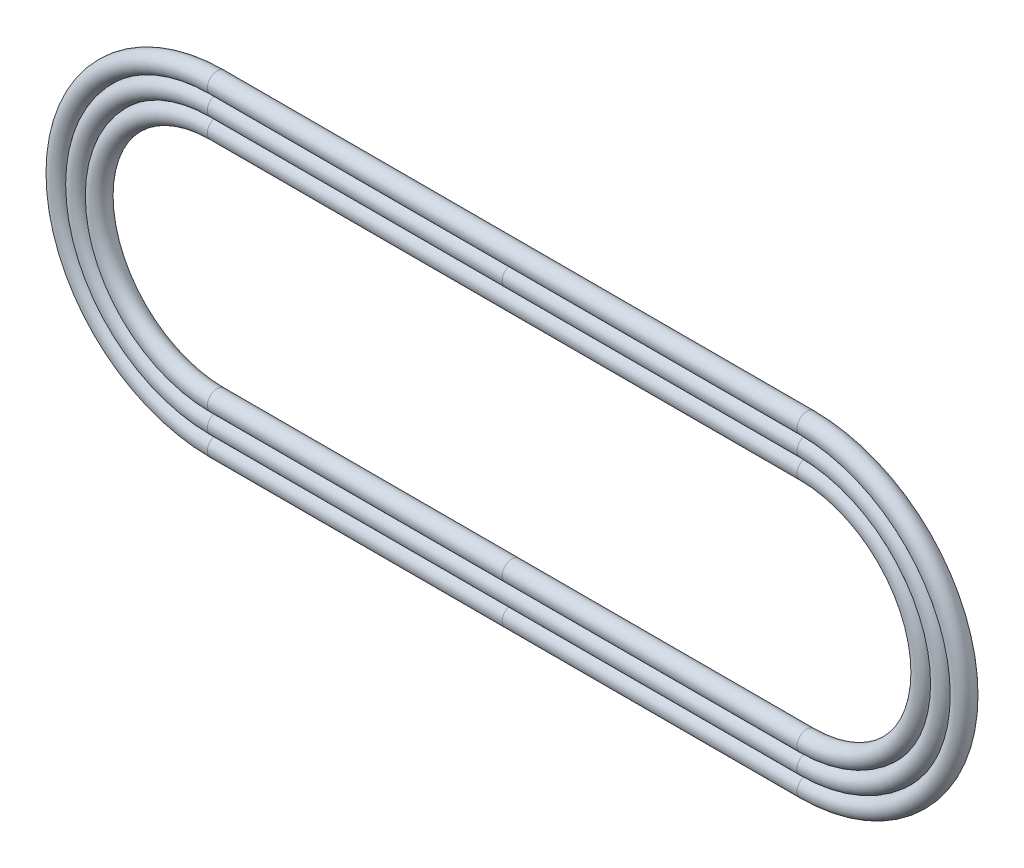
SolidWorks part; units mm, degrees
ref_plane "Front Plane" through (0, 0, 0) normal (0, 0, 1) x (1, 0, 0)
ref_plane "Top Plane" through (0, 0, 0) normal (0, 1, 0) x (1, 0, 0)
ref_plane "Right Plane" through (0, 0, 0) normal (1, 0, 0) x (0, 0, -1)
sketch "Sketch30" plane through (0, 0, 0) normal (0, 0, 1) x (1, 0, 0)
  line L0 (-1500, 0) -> (1500, 0) construction
  line L1 (-1500, 800) -> (1500, 800)
  line L2 (-1500, -800) -> (1500, -800)
  arc A0 (-1500, 800) -> (-1500, -800) centre (-1500, 0) ccw
  arc A1 (1500, -800) -> (1500, 800) centre (1500, 0) ccw
  point P2 (0, 0)
  dimension "D2" = 800
  dimension "D1" = 3000
sketch "Sketch31" plane through (0, 0, 0) normal (1, 0, 0) x (0, 0, -1)
  line L0 (0, 800) -> (0, -800) construction
  line L1 (0, 800) -> (0, -800) construction
  circle A0 centre (0, -800) radius 50
  dimension "D1" = 100
sweep "Sweep1" add profiles "Sketch31" path "Sketch30"
sketch "Sketch32" plane through (0, 0, 0) normal (0, 0, 1) x (1, 0, 0)
  line L0 (-1500, 0) -> (1500, 0) construction
  line L1 (-1500, 700) -> (1500, 700)
  line L2 (-1500, -700) -> (1500, -700)
  arc A0 (-1500, 700) -> (-1500, -700) centre (-1500, 0) ccw
  arc A1 (1500, -700) -> (1500, 700) centre (1500, 0) ccw
  point P2 (0, 0)
  dimension "D2" = 700
  dimension "D1" = 3000
sketch "Sketch33" plane through (0, 0, 0) normal (1, 0, 0) x (0, 0, -1)
  line L0 (0, 700) -> (0, -700) construction
  line L1 (0, 700) -> (0, -700) construction
  circle A0 centre (0, 700) radius 50
  point P6 (0, 0)
  dimension "D1" = 100
sweep "Sweep2" add profiles "Sketch33" path "Sketch32"
sketch "Sketch34" plane through (0, 0, 0) normal (0, 0, 1) x (1, 0, 0)
  line L0 (-1500, 0) -> (1500, 0) construction
  line L1 (-1500, 600) -> (1500, 600)
  line L2 (-1500, -600) -> (1500, -600)
  arc A0 (-1500, 600) -> (-1500, -600) centre (-1500, 0) ccw
  arc A1 (1500, -600) -> (1500, 600) centre (1500, 0) ccw
  point P2 (0, 0)
  dimension "D2" = 600
  dimension "D1" = 3000
sketch "Sketch35" plane through (0, 0, 0) normal (1, 0, 0) x (0, 0, -1)
  line L0 (0, 600) -> (0, -600) construction
  line L1 (0, 600) -> (0, -600) construction
  circle A0 centre (0, -600) radius 50
  point P6 (0, 0)
  dimension "D1" = 100
sweep "Sweep3" add profiles "Sketch35" path "Sketch34"
